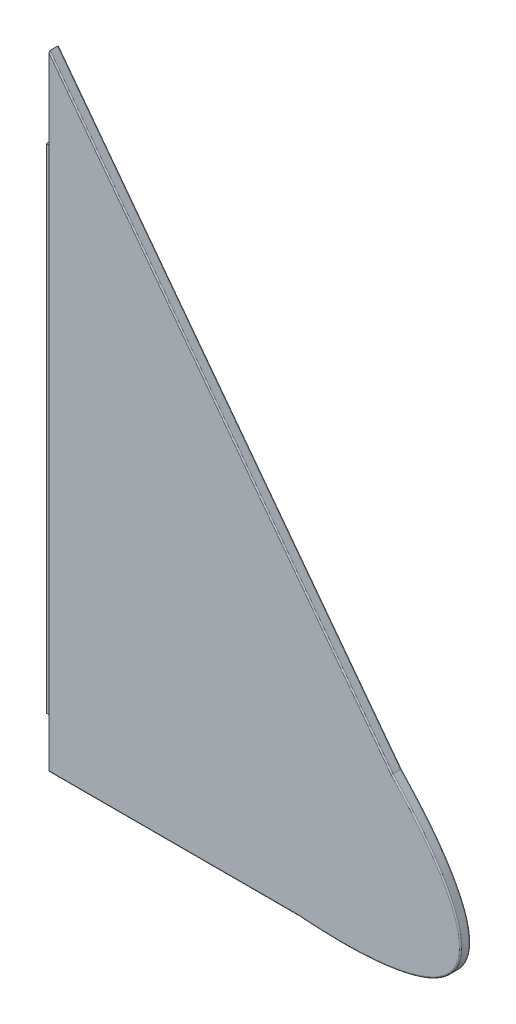
SolidWorks part; units mm, degrees
material "ABS"
ref_plane "Front Plane" through (0, 0, 0) normal (0, 0, 1) x (1, 0, 0)
ref_plane "Top Plane" through (0, 0, 0) normal (0, 1, 0) x (1, 0, 0)
ref_plane "Right Plane" through (0, 0, 0) normal (1, 0, 0) x (0, 0, -1)
ref_plane "Plane1" through (0, 0, 3) normal (0, 0, 1) x (1, 0, 0)
sketch "Sketch1" plane through (0, 0, 3) normal (0, 0, 1) x (1, 0, 0)
  line L0 (28.2435, 13.9546) -> (0, 51.435)
  line L1 (0, 51.435) -> (0, 0)
  line L2 (0, 0) -> (20.574, 0)
  spline S0 degree 3 poles (28.2435, 13.9546) (28.2554, 13.9418) (28.2672, 13.9291) (28.279, 13.9163) (30.1533, 11.8947) (32.0065, 9.7448) (33.1642, 7.2429) (33.4018, 6.7296) (33.6049, 6.1959) (33.739, 5.6464) (33.8743, 5.0918) (33.9399, 4.5056) (33.8715, 3.9389) (33.8276, 3.5751) (33.7255, 3.2127) (33.5647, 2.8835) (33.4038, 2.5539) (33.1809, 2.2503) (32.9222, 1.9904) (32.5652, 1.6316) (32.1337, 1.3432) (31.683, 1.1129) (30.8468, 0.6857) (29.9221, 0.4313) (28.9998, 0.255) (26.2399, -0.2726) (23.3775, -0.1887) (20.574, 0) knots 0.079809 0.079809 0.079809 0.079809 0.079859 0.079859 0.079859 0.087953 0.087953 0.087953 0.089587 0.089587 0.089587 0.091249 0.091249 0.091249 0.092309 0.092309 0.092309 0.09337 0.09337 0.09337 0.094836 0.094836 0.094836 0.097566 0.097566 0.097566 0.105821 0.105821 0.105821 0.105821
  dimension "D1" = 20.574
extrude "Boss-Extrude1" add sketch "Sketch1" against normal blind 0.8
fillet "Fillet1" radius 0.1 8 edges at (10.287, 0, 2.2) (14.1218, 32.6948, 2.2) (10.287, 0, 3) (14.1218, 32.6948, 3) (20.574, 0, 2.6) (28.2435, 13.9546, 2.6)
sketch "Sketch4" plane through (0, 0, 0) normal (-1, 0, 0) x (0, 0, 1)
  line L0 (2.3, 0) -> (2.9, 0) construction
  line L1 (2.4666, 44.45) -> (2.7206, 44.45)
  line L2 (2.4666, 44.45) -> (2.4666, 3.81)
  line L3 (2.4666, 3.81) -> (2.7206, 3.81)
  line L4 (2.7206, 44.45) -> (2.7206, 3.81)
  line L5 (3, 51.2688) -> (3, 0.1) construction
  dimension "D1" = 40.64
  dimension "D2" = 0.254
  dimension "D3" = 3.81
  dimension "D4" = 0.2794
extrude "Boss-Extrude3" add sketch "Sketch4" along normal blind 0.5
